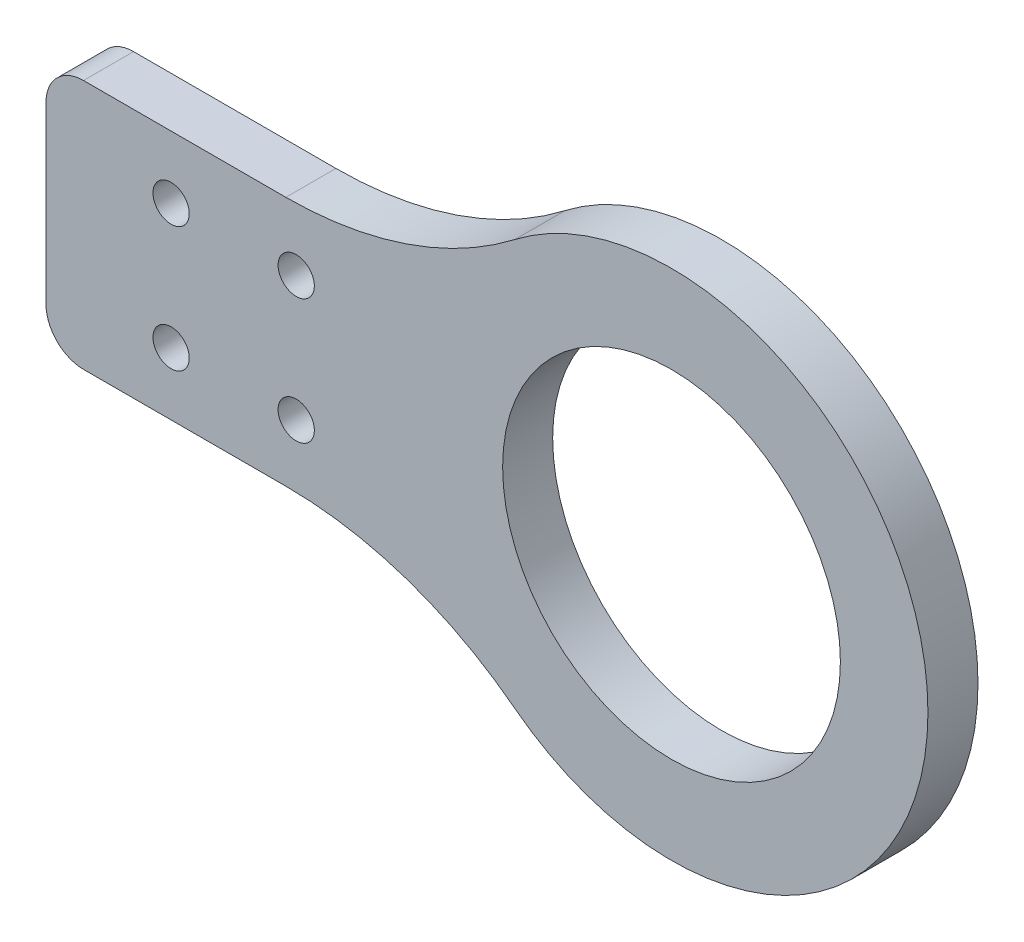
SolidWorks part; units mm, degrees
material "Thornel Mat VMA"
ref_plane "前视基准面" through (0, 0, 0) normal (0, 0, 1) x (1, 0, 0)
ref_plane "上视基准面" through (0, 0, 0) normal (0, 1, 0) x (1, 0, 0)
ref_plane "右视基准面" through (0, 0, 0) normal (1, 0, 0) x (0, 0, -1)
other "Configuration Table"
sketch "草图1" plane through (0, 0, 0) normal (0, 0, 1) x (1, 0, 0)
  line L0 (0, -10) -> (17.8955, -10) construction
  line L1 (0, 0) -> (-48.5259, 0) construction
  line L2 (0, 0) -> (0, -20) construction
  line L3 (0, -20) -> (-48.5259, -20) construction
  line L4 (-48.5259, 0) -> (-48.5259, -20) construction
  line L5 (0, 0) -> (-32.1045, 0)
  line L6 (-32.1045, 0) -> (-32.1045, -20)
  line L7 (-32.1045, -20) -> (0, -20)
  line L8 (-2.1045, 0) -> (-2.1045, -20) construction
  circle A0 centre (17.8955, -10) radius 13.5
  arc A1 (0, -20) -> (0, 0) centre (17.8955, -10) ccw
  dimension "D2" = 27
  dimension "D3" = 7
  dimension "D1" = 20
  dimension "D4" = 30
  dimension "D5" = 20
extrude "凸台-拉伸1" add sketch "草图1" along normal blind 4
sketch "草图2" plane through (0, 0, 4) normal (0, 0, 1) x (1, 0, 0)
  line L0 (-32.1045, -5) -> (5.3556, -5) construction
  line L1 (-32.1045, 0) -> (-32.1045, -20) construction
  line L2 (0, 0) -> (-32.1045, 0) construction
  line L3 (-22.1045, -5) -> (-12.1045, -5) construction
  line L4 (-22.1045, -5) -> (-22.1045, -15) construction
  circle A1 centre (-22.1045, -5) radius 1.45
  circle A4 centre (17.8955, -10) radius 13.5 construction
  circle A5 centre (-12.1045, -5) radius 1.45
  circle A7 centre (-12.1045, -15) radius 1.45
  circle A9 centre (-22.1045, -15) radius 1.45
  circle A10 centre (-2.1045, -5) radius 1.45 [skipped]
  circle A11 centre (-2.1045, -15) radius 1.45 [skipped]
  dimension "D1" = 2.9
  dimension "D2" = 10
  dimension "D4" = 2
  dimension "D5" = 5
  dimension "D6" = 10
  dimension "D7" = 10
  dimension "D3" = 3
extrude "切除-拉伸1" cut sketch "草图2" against normal through all
fillet "圆角1" radius 30 2 edges at (0, -20, 2) (0, 0, 2)
fillet "圆角2" radius 3 2 edges at (-32.1045, -20, 2) (-32.1045, 0, 2)
